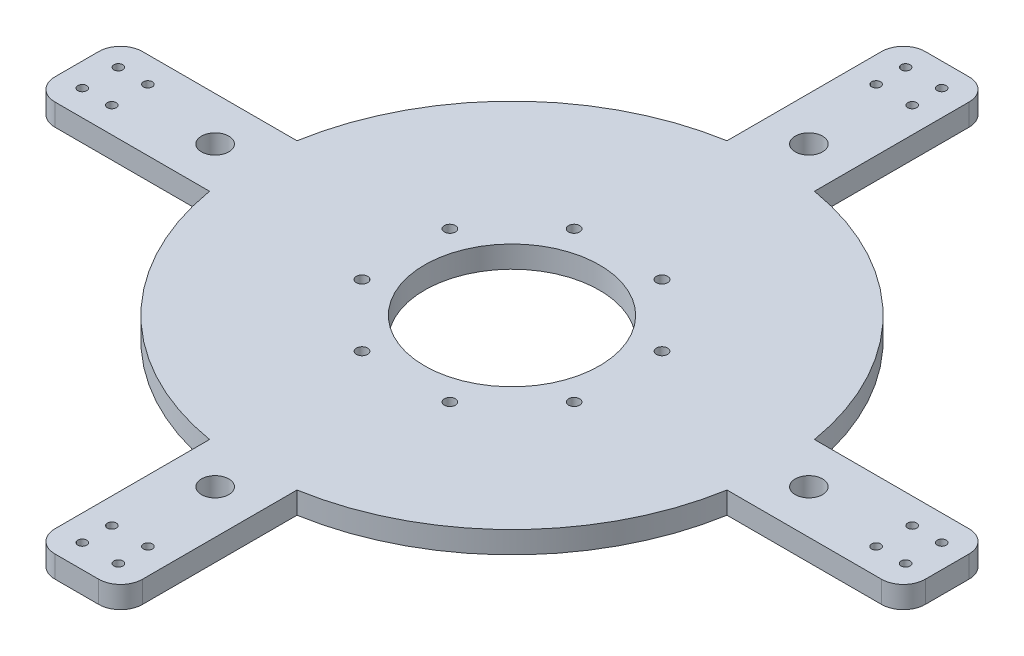
SolidWorks part; units mm, degrees
ref_plane "Front Plane" through (0, 0, 0) normal (0, 0, 1) x (1, 0, 0)
ref_plane "Top Plane" through (0, 0, 0) normal (0, 1, 0) x (1, 0, 0)
ref_plane "Right Plane" through (0, 0, 0) normal (1, 0, 0) x (0, 0, -1)
sketch "Sketch1" plane through (0, 0, 0) normal (0, 1, 0) x (1, 0, 0)
  circle A0 centre (0, 0) radius 200
  dimension "D1" = 400
extrude "Boss-Extrude1" add sketch "Sketch1" along normal blind 10
sketch "Sketch2" plane through (0, 10, 0) normal (0, 1, 0) x (1, 0, 0)
  line L0 (0, 135.7645) -> (135.7645, 0) construction
  line L1 (135.7645, 0) -> (0, -135.7645) construction
  line L2 (0, -135.7645) -> (-135.7645, 0) construction
  line L3 (-135.7645, 0) -> (0, 135.7645) construction
  line L4 (0, 0) -> (67.8823, 67.8823) construction
  line L5 (0, 0) -> (0, 55.7409) construction
  circle A0 centre (-135.7645, 0) radius 6.25
  circle A1 centre (0, -135.7645) radius 6.25
  circle A2 centre (135.7645, 0) radius 6.25
  circle A4 centre (0, 135.7645) radius 6.25
  dimension "D13" = 12.5
  dimension "D2" = 12.5
  dimension "D3" = 12.5
  dimension "D4" = 12.5
  dimension "D14" = 96
  dimension "D15" = 192
  dimension "D16" = 192
  dimension "D17" = 96
  dimension "D18" = 45
extrude "Cut-Extrude1" cut sketch "Sketch2" against normal through all
sketch "Sketch3" plane through (0, 0, 0) normal (1, 0, 0) x (0, 0, -1)
  line L0 (0, 0) -> (0, 10) construction
  line L1 (200, 10) -> (-200, 10) construction
sketch "Sketch4" plane through (0, 10, 0) normal (0, 1, 0) x (1, 0, 0)
  line L0 (0, 0) -> (0, 54.9076) construction
  line L1 (0, 0) -> (21.5205, 51.955) construction
  circle A0 centre (20.0909, 48.5037) radius 2.55
  dimension "D2" = 5.1
  dimension "D1" = 22.5
  dimension "D3" = 52.5
extrude "Cut-Extrude2" cut sketch "Sketch4" against normal through all
pattern_circular "CirPattern1" count 8 over 360 about axis through (0, 0, 0) along (0, 1, 0) of "Cut-Extrude2"
sketch "Sketch5" plane through (0, 10, 0) normal (0, 1, 0) x (1, 0, 0)
  line L0 (0, 0) -> (-200, 0) construction
  line L1 (-188.2645, 8.25) -> (-188.2645, -8.25) construction
  line L2 (-174.7645, 8.25) -> (-174.7645, -8.25) construction
  line L3 (-188.2645, 8.25) -> (-174.7645, 8.25) construction
  line L4 (-188.2645, -8.25) -> (-174.7645, -8.25) construction
  line L5 (-135.7645, 6.25) -> (-135.7645, -5.8775) construction
  circle A0 centre (0, 0) radius 200 construction
  circle A1 centre (-188.2645, 8.25) radius 2.05
  circle A2 centre (-174.7645, 8.25) radius 2.05
  circle A3 centre (-174.7645, -8.25) radius 2.05
  circle A4 centre (-188.2645, -8.25) radius 2.05
  circle A5 centre (-135.7645, 0) radius 6.25 construction
  dimension "D4" = 4.1
  dimension "D5" = 4.1
  dimension "D6" = 4.1
  dimension "D7" = 4.1
  dimension "D1" = 13.5
  dimension "D2" = 8.25
  dimension "D3" = 8.25
  dimension "D8" = 39
extrude "Cut-Extrude3" cut sketch "Sketch5" against normal through all
pattern_circular "CirPattern2" count 4 over 360 about axis through (0, 0, 0) along (0, 1, 0) of "Cut-Extrude3"
sketch "Sketch6" plane through (0, 10, 0) normal (0, 1, 0) x (1, 0, 0)
  line L0 (0, 0) -> (-200, 0) construction
  line L1 (0, 0) -> (0, 200) construction
  line L2 (-41.0025, 20) -> (-198.9975, 20)
  line L3 (-41.0025, 20) -> (-41.0025, -20)
  line L4 (-41.0025, -20) -> (-198.9975, -20)
  line L5 (-198.9975, 20) -> (-198.9975, -20)
  line L6 (-41.0025, 20) -> (-198.9975, -20) construction
  line L7 (-41.0025, -20) -> (-198.9975, 20) construction
  line L9 (-20, 41.0025) -> (20, 41.0025)
  line L10 (-20, 41.0025) -> (-20, 198.9975)
  line L11 (-20, 198.9975) -> (20, 198.9975)
  line L12 (20, 41.0025) -> (20, 198.9975)
  line L13 (-20, 41.0025) -> (20, 198.9975) construction
  line L14 (-20, 198.9975) -> (20, 41.0025) construction
  circle A0 centre (0, 0) radius 120
  circle A1 centre (0, 0) radius 200 construction
  point P3 (-120, 0)
  point P12 (0, 120)
  circle M30 centre (0, 0) radius 200
  dimension "D1" = 240
  dimension "D2" = 40
  dimension "D3" = 40
extrude "Cut-Extrude4" cut sketch "Sketch6" against normal blind 10 contours A0 L10 L2 M30 | L5 M30
pattern_circular "CirPattern3" count 4 every 90 about axis through (0, 0, 0) along (0, 1, 0) of "Cut-Extrude4"
sketch "Sketch7" plane through (0, 10, 0) normal (0, 1, 0) x (1, 0, 0)
  circle A0 centre (0, 0) radius 40
  dimension "D1" = 80
extrude "Cut-Extrude5" cut sketch "Sketch7" against normal through all
fillet "Fillet1" radius 10 8 edges at (-198.9975, 5, -20) (-198.9975, 5, 20) (20, 5, -198.9975) (-20, 5, -198.9975) (198.9975, 5, -20) (198.9975, 5, 20) (20, 5, 198.9975) (-20, 5, 198.9975)
